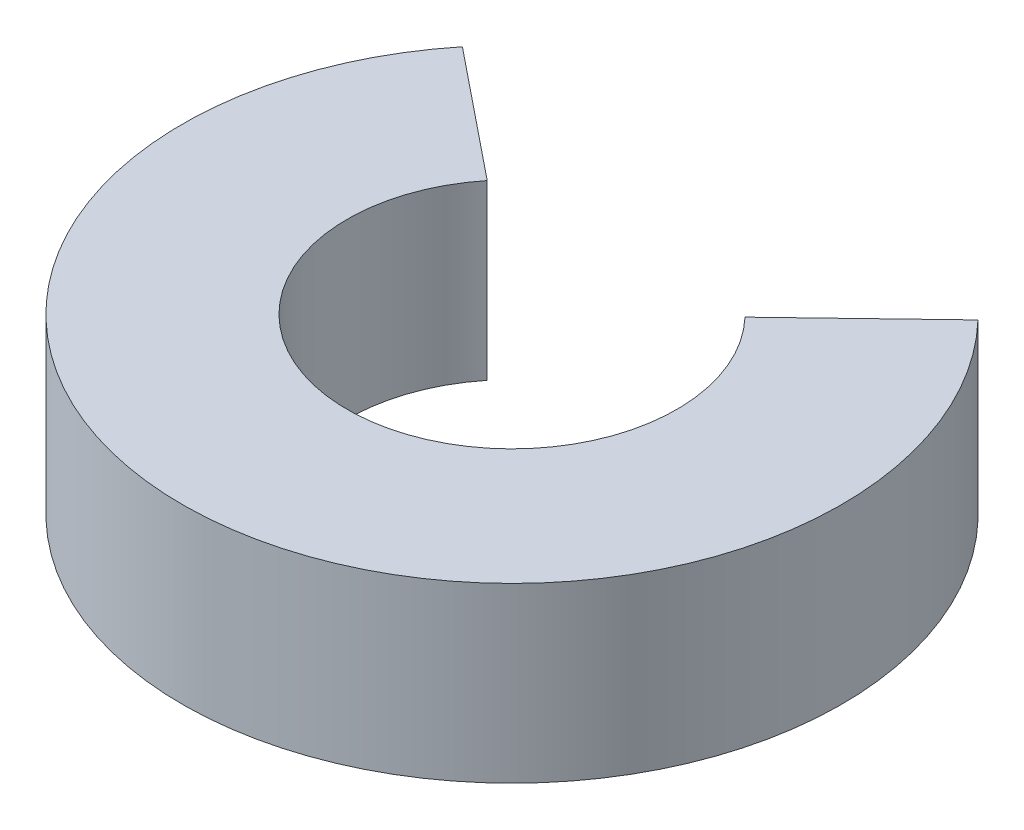
SolidWorks part; units mm, degrees
ref_plane "Plan de face" through (0, 0, 0) normal (0, 0, 1) x (1, 0, 0)
ref_plane "Plan de dessus" through (0, 0, 0) normal (0, 1, 0) x (1, 0, 0)
ref_plane "Plan de droite" through (0, 0, 0) normal (1, 0, 0) x (0, 0, -1)
sketch "Esquisse1" plane through (0, 0, 0) normal (0, 1, 0) x (1, 0, 0)
  line L0 (-6.2268, 5.0227) -> (-3.1134, 2.5113)
  line L1 (2.8866, 2.769) -> (5.7732, 5.538)
  arc A0 (-3.1134, 2.5113) -> (2.8866, 2.769) centre (0, 0) ccw
  arc A1 (-6.2268, 5.0227) -> (5.7732, 5.538) centre (0, 0) ccw
  dimension "D1" = 8
  dimension "D2" = 16
  dimension "D3" = 6
extrude "Boss.-Extru.1" add sketch "Esquisse1" along normal blind 4.2
